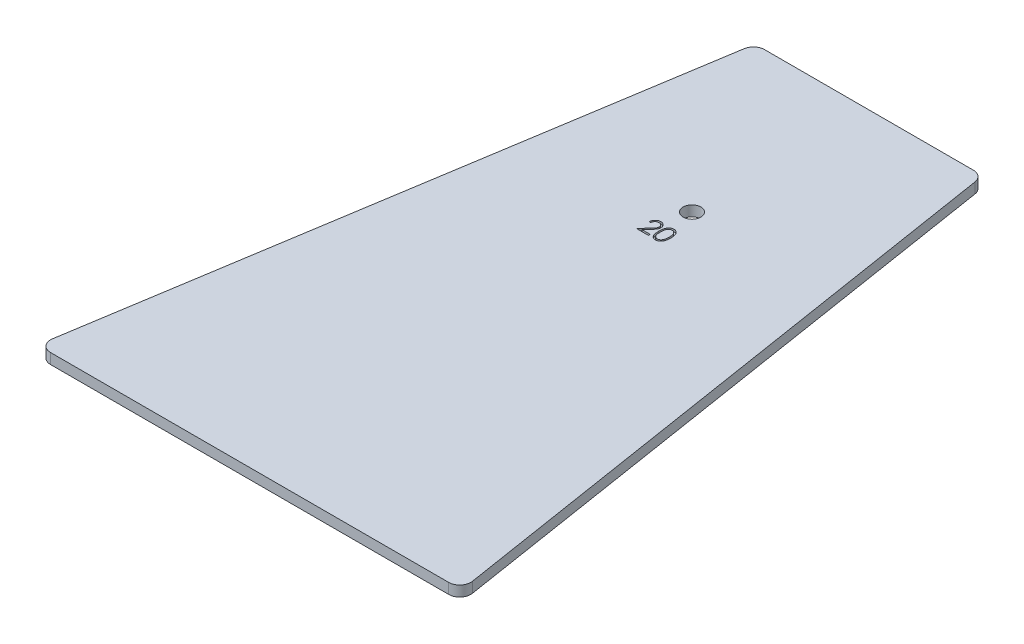
SolidWorks part; units mm, degrees
material "Acrylic (Medium-high impact)"
ref_plane "Front Plane" through (0, 0, 0) normal (0, 0, 1) x (1, 0, 0)
ref_plane "Top Plane" through (0, 0, 0) normal (0, 1, 0) x (1, 0, 0)
ref_plane "Right Plane" through (0, 0, 0) normal (1, 0, 0) x (0, 0, -1)
sketch "Sketch1" plane through (0, 0, 0) normal (0, 1, 0) x (1, 0, 0)
  line L0 (0, 0) -> (0, -355.6) construction
  line L1 (-65.405, 0) -> (65.405, 0)
  line L2 (65.405, 0) -> (121.7265, -355.6)
  line L3 (121.7265, -355.6) -> (-121.7265, -355.6)
  line L4 (-65.405, 0) -> (-121.7265, -355.6)
  dimension "D1" = 355.6
  dimension "D2" = 18
  dimension "D3" = 130.81
extrude "Boss-Extrude1" add sketch "Sketch1" along normal blind 5.9944
sketch "Sketch2" plane through (0, 5.9944, 0) normal (0, 1, 0) x (1, 0, 0)
  line L0 (0, 0) -> (0, -101.6) construction
  line L1 (65.405, 0) -> (-65.405, 0) construction
  circle A0 centre (0, -101.6) radius 5.08
  dimension "D1" = 10.16
  dimension "D2" = 101.6
extrude "Cut-Extrude1" cut sketch "Sketch2" against normal through all
sketch "Sketch3" plane through (0, 5.9944, 0) normal (0, 1, 0) x (1, 0, 0)
  line L0 (0, -101.6) -> (0, -114.3) construction
  line L2 (8.255, -125.73) -> (8.255, -114.3) construction
  line L3 (8.255, -125.73) -> (-8.255, -125.73) construction
  line L4 (8.255, -114.3) -> (-8.255, -114.3) construction
  line L5 (-8.255, -125.73) -> (-8.255, -114.3) construction
  line L6 (8.255, -125.73) -> (-8.255, -114.3) construction
  line L7 (8.255, -114.3) -> (-8.255, -125.73) construction
  text T0 "20" font "Century Gothic" height 10.16
  point P4 (0, -120.015)
  dimension "D1" = 11.43
  dimension "D2" = 12.7
  dimension "D3" = 16.51
extrude "Cut-Extrude2" cut sketch "Sketch3" against normal blind 1.27
fillet "Fillet1" radius 6.35 4 edges at (121.7265, 2.9972, 355.6) (-121.7265, 2.9972, 355.6) (-65.405, 2.9972, 0) (65.405, 2.9972, 0)
